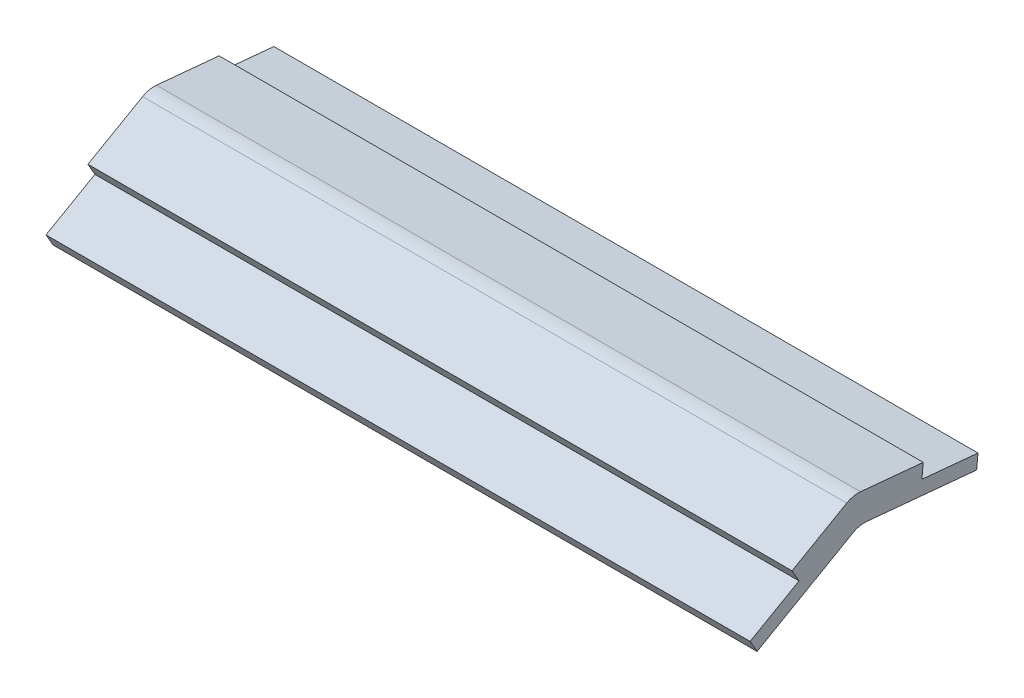
SolidWorks part; units mm, degrees
ref_plane "Front Plane" through (0, 0, 0) normal (0, 0, 1) x (1, 0, 0)
ref_plane "Top Plane" through (0, 0, 0) normal (0, 1, 0) x (1, 0, 0)
ref_plane "Right Plane" through (0, 0, 0) normal (1, 0, 0) x (0, 0, -1)
sketch "Sketch1" plane through (0, 0, 0) normal (1, 0, 0) x (0, 0, -1)
  line L6 (-17.0368, 11.1635) -> (-15.5482, 8.5588)
  line L7 (-17.0368, 11.1635) -> (-5.3884, 17.8204)
  line L8 (-2.4369, 18.4571) -> (10.9199, 17.1944)
  line L9 (10.9199, 17.1944) -> (10.6376, 14.2078)
  line L12 (-4.0135, 18.6062) -> (0, 0) construction
  line L13 (-15.5482, 8.5588) -> (-25.9669, 2.6047)
  line L14 (-25.9669, 2.6047) -> (-24.4783, 0)
  line L15 (-24.4783, 0) -> (-4.0613, 11.6681)
  line L16 (-1.1098, 12.3049) -> (22.302, 10.0916)
  line L18 (10.6376, 14.2078) -> (22.5843, 13.0783)
  line L19 (22.5843, 13.0783) -> (22.302, 10.0916)
  line L20 (0, 0) -> (50000, 0) construction
  arc A0 (-2.4369, 18.4571) -> (-5.3884, 17.8204) centre (-2.9075, 13.4793) ccw
  arc A1 (-1.1098, 12.3049) -> (-4.0613, 11.6681) centre (-1.5804, 7.327) ccw
  point P5 (-16.1865, 11.5178)
  point P15 (0, 0)
  point P16 (6.3771, 13.0553)
  point P17 (0, 0)
  point P23 (-2.6864, 12.4539)
  dimension "D12" = 5
  dimension "D13" = 5
  dimension "D1" = 15
  dimension "D2" = 15
  dimension "D3" = 144.852
  dimension "D4" = 72.425
  dimension "D5" = 12
  dimension "D6" = 12
  dimension "D7" = 3
  dimension "D8" = 3
  dimension "D9" = 3
  dimension "D10" = 3
  dimension "D11" = 77.827
extrude "Boss-Extrude1" add sketch "Sketch1" along normal blind 150
